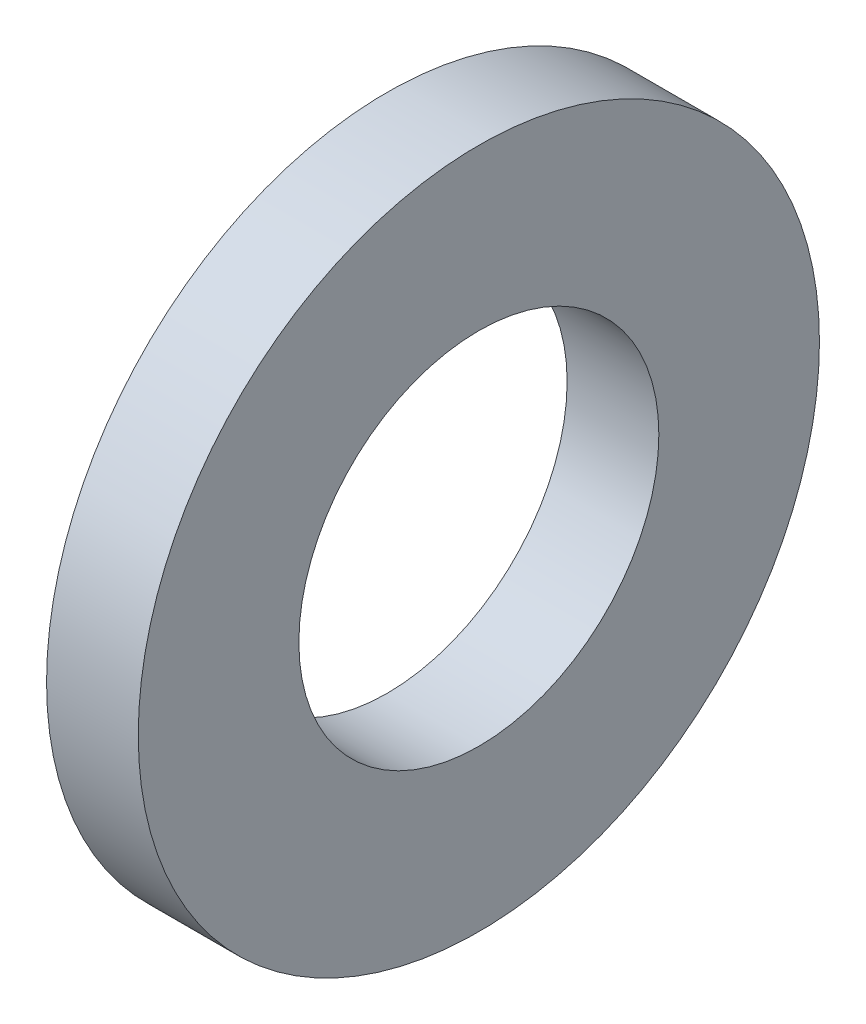
SolidWorks part; units mm, degrees
ref_plane "Plane1" through (0, 0, 0) normal (0, 0, 1) x (1, 0, 0)
ref_plane "Plane2" through (0, 0, 0) normal (0, 1, 0) x (1, 0, 0)
ref_plane "Plane3" through (0, 0, 0) normal (1, 0, 0) x (0, 0, -1)
sketch "Sketch1" plane through (0, 0, 0) normal (0, 0, 1) x (1, 0, 0)
  line L0 (-34.925, 0) -> (9.525, 0) construction
  line L1 (0, 3.435) -> (0, 6.5)
  line L2 (0, 6.5) -> (-1.75, 6.5)
  line L3 (-1.75, 6.5) -> (-1.75, 3.435)
  line L4 (-1.75, 3.435) -> (0, 3.435)
  dimension "Thickness" = 1.75
  dimension "Inside_dia" = 6.87
  dimension "Outside_dia" = 13
revolve "Base-Revolve" add sketch "Sketch1" angle 360 about L0
